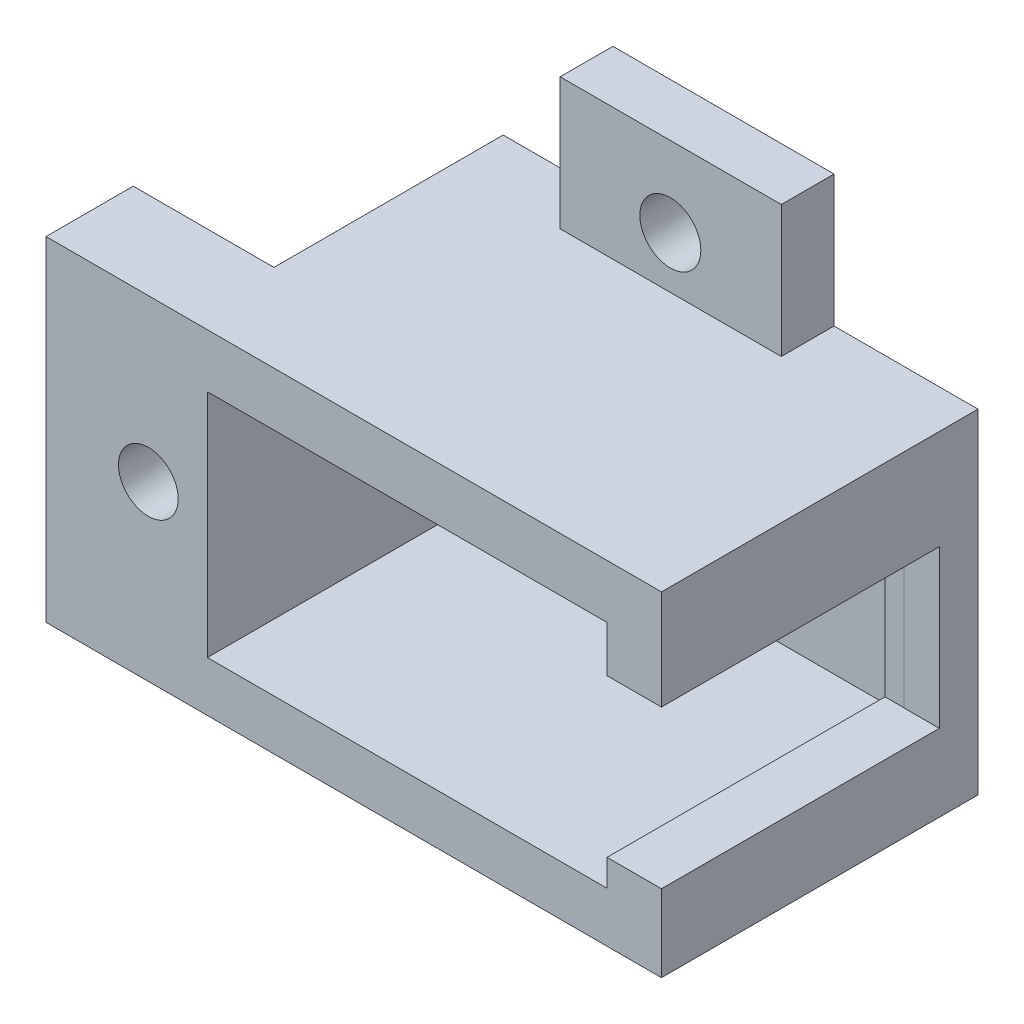
SolidWorks part; units mm, degrees
ref_plane "Front Plane" through (0, 0, 0) normal (0, 0, 1) x (1, 0, 0)
ref_plane "Top Plane" through (0, 0, 0) normal (0, 1, 0) x (1, 0, 0)
ref_plane "Right Plane" through (0, 0, 0) normal (1, 0, 0) x (0, 0, -1)
sketch "Sketch1" plane through (0, 0, 0) normal (0, 0, 1) x (1, 0, 0)
  line L1 (-1.0933, 0.8351) -> (1.4067, 0.8351)
  line L2 (-1.0933, 0.8351) -> (-1.0933, -0.6649)
  line L3 (-1.0933, -0.6649) -> (1.4067, -0.6649)
  line L4 (1.4067, 0.8351) -> (1.4067, -0.6649)
  dimension "D1" = 2.5
  dimension "D2" = 1.5
extrude "Boss-Extrude1" add sketch "Sketch1" along normal blind 1.8
sketch "Sketch2" plane through (0, 0, 1.8) normal (0, 0, 1) x (1, 0, 0)
  line L1 (-0.9755, 0.7298) -> (1.2972, 0.7298)
  line L2 (-0.9755, 0.7298) -> (-0.9755, -0.5795)
  line L3 (-0.9755, -0.5795) -> (1.2972, -0.5795)
  line L4 (1.2972, 0.7298) -> (1.2972, -0.5795)
extrude "Cut-Extrude1" cut sketch "Sketch2" against normal blind 1.7
sketch "Sketch3" plane through (1.4067, 0, 0) normal (1, 0, 0) x (0, 0, -1)
  line L1 (-0.2922, -0.4617) -> (-0.2902, -0.4617)
  line L2 (-0.2922, -0.4617) -> (-0.2922, -0.459)
  line L3 (-0.2922, -0.459) -> (-0.2902, -0.459)
  line L4 (-0.2902, -0.4617) -> (-0.2902, -0.459)
  line L5 (-0.2193, -0.427) -> (-1.6684, -0.427)
  line L6 (-0.2193, -0.427) -> (-0.2193, 0.4688)
  line L7 (-0.2193, 0.4688) -> (-1.6684, 0.4688)
  line L8 (-1.6684, -0.427) -> (-1.6684, 0.4688)
extrude "Cut-Extrude2" cut sketch "Sketch3" against normal blind 1.8
scale "Scale1" scale about centroid uniform scaling yes scale factor 10
sketch "Sketch6" plane through (13.765, 0, 0) normal (1, 0, 0) x (0, 0, -1)
  line L0 (-10.0899, -5.3785) -> (4.4011, -5.3785) construction
  line L1 (-12.7162, 3.5683) -> (-9.3169, 3.5683)
  line L2 (-12.7162, 3.5683) -> (-12.7162, -5.3785)
  line L3 (-12.7162, -5.3785) -> (-9.3169, -5.3785)
  line L4 (-9.3169, 3.5683) -> (-9.3169, -5.3785)
extrude "Cut-Extrude4" cut sketch "Sketch6" against normal blind 10
sketch "Sketch12" plane through (-11.235, 0, 0) normal (-1, 0, 0) x (0, 0, 1)
  line L1 (11.4058, 7.2418) -> (-6.5942, 7.2418) construction
  line L3 (6.4439, 7.2418) -> (11.4058, 7.2418)
  line L4 (6.4439, 7.2418) -> (6.4439, -7.7582)
  line L5 (6.4439, -7.7582) -> (11.4058, -7.7582)
  line L6 (11.4058, 7.2418) -> (11.4058, -7.7582)
extrude "Boss-Extrude5" add sketch "Sketch12" along normal blind 8
sketch "Sketch13" plane through (0, 0, 11.4058) normal (0, 0, 1) x (1, 0, 0)
  circle A0 centre (-13.4157, 0.0718) radius 1.6988
extrude "Cut-Extrude6" cut sketch "Sketch13" against normal blind 34 contours A0
sketch "Sketch22" plane through (0, 0, -6.5942) normal (0, 0, -1) x (-1, 0, 0)
  line L0 (-13.765, 7.2418) -> (11.235, 7.2418) construction
  line L1 (-7.5797, 7.2418) -> (5, 7.2418)
  line L2 (-7.5797, 7.2418) -> (-7.5797, 16.7274)
  line L3 (-7.5797, 16.7274) -> (5, 16.7274)
  line L4 (5, 7.2418) -> (5, 16.7274)
  line L5 (-13.765, -0.2582) -> (11.235, -0.2582) construction
  line L6 (-13.765, -7.7582) -> (-13.765, 7.2418) construction
  line L7 (11.235, 7.2418) -> (11.235, -7.7582) construction
  line L8 (-7.5797, -17.2437) -> (5, -17.2437)
  line L9 (5, -7.7582) -> (5, -17.2437)
  line L10 (-7.5797, -7.7582) -> (5, -7.7582)
  line L11 (-7.5797, -7.7582) -> (-7.5797, -17.2437)
extrude "Boss-Extrude10" add sketch "Sketch22" against normal blind 3
sketch "Sketch25" plane through (0, 0, -3.5942) normal (0, 0, 1) x (1, 0, 0)
  line L0 (-10.0573, -0.3569) -> (12.6698, -0.3569) construction
  line L1 (-10.0573, 6.1898) -> (-10.0573, -6.9036) construction
  line L2 (12.6698, -6.9036) -> (12.6698, 6.1898) construction
  circle A0 centre (1.2686, 12.1797) radius 1.7335
  circle A1 centre (1.2686, -12.8935) radius 1.7335
extrude "Cut-Extrude7" cut sketch "Sketch25" against normal blind 36
sketch "Sketch26" plane through (0, 7.2418, 0) normal (0, 1, 0) x (1, 0, 0)
  line L0 (13.765, -11.4058) -> (-19.235, -11.4058) construction
  line L1 (-11.235, 6.5942) -> (-4.9881, 6.5942)
  line L2 (-11.235, 6.5942) -> (-11.235, -11.4058)
  line L3 (-11.235, -11.4058) -> (-4.9881, -11.4058)
  line L4 (-4.9881, 6.5942) -> (-4.9881, -11.4058)
extrude "Boss-Extrude11" add sketch "Sketch26" along normal blind 2
sketch "Sketch27" plane through (0, 7.2418, 0) normal (0, 1, 0) x (1, 0, 0)
  line L0 (13.765, -11.4058) -> (-4.9881, -11.4058) construction
  line L1 (13.765, 6.5942) -> (7.5802, 6.5942)
  line L2 (13.765, 6.5942) -> (13.765, -11.4058)
  line L3 (13.765, -11.4058) -> (7.5802, -11.4058)
  line L4 (7.5802, 6.5942) -> (7.5802, -11.4058)
extrude "Boss-Extrude12" add sketch "Sketch27" along normal blind 2
sketch "Sketch28" plane through (0, 7.2418, 0) normal (0, 1, 0) x (1, 0, 0)
  line L1 (-5, 3.5942) -> (7.5802, 3.5942)
  line L2 (-5, 3.5942) -> (-5, -11.4058)
  line L3 (-5, -11.4058) -> (7.5802, -11.4058)
  line L4 (7.5802, 3.5942) -> (7.5802, -11.4058)
extrude "Boss-Extrude13" add sketch "Sketch28" along normal blind 2
sketch "Sketch29" plane through (0, -7.7582, 0) normal (0, -1, 0) x (-1, 0, 0)
  line L0 (19.235, -11.4058) -> (-13.765, -11.4058) construction
  line L1 (11.235, 6.5942) -> (5.0179, 6.5942)
  line L2 (11.235, 6.5942) -> (11.235, -11.4058)
  line L3 (11.235, -11.4058) -> (5.0179, -11.4058)
  line L4 (5.0179, 6.5942) -> (5.0179, -11.4058)
extrude "Boss-Extrude14" add sketch "Sketch29" along normal blind 2
sketch "Sketch30" plane through (0, -7.7582, 0) normal (0, -1, 0) x (-1, 0, 0)
  line L0 (5.0179, -11.4058) -> (-13.765, -11.4058) construction
  line L1 (-13.765, 6.5942) -> (-7.6155, 6.5942)
  line L2 (-13.765, 6.5942) -> (-13.765, -11.4058)
  line L3 (-13.765, -11.4058) -> (-7.6155, -11.4058)
  line L4 (-7.6155, 6.5942) -> (-7.6155, -11.4058)
extrude "Boss-Extrude15" add sketch "Sketch30" along normal blind 2
sketch "Sketch31" plane through (0, -7.7582, 0) normal (0, -1, 0) x (1, 0, 0)
  line L1 (-5.0179, 11.4058) -> (7.5797, 11.4058)
  line L2 (-5.0179, 11.4058) -> (-5.0179, -3.5942)
  line L3 (-5.0179, -3.5942) -> (7.5797, -3.5942)
  line L4 (7.5797, 11.4058) -> (7.5797, -3.5942)
extrude "Boss-Extrude16" add sketch "Sketch31" along normal blind 2
sketch "Sketch32" plane through (0, 7.2418, 0) normal (0, 1, 0) x (1, 0, 0)
  line L1 (-19.235, -6.4439) -> (-11.235, -6.4439)
  line L2 (-19.235, -6.4439) -> (-19.235, -11.4058)
  line L3 (-19.235, -11.4058) -> (-11.235, -11.4058)
  line L4 (-11.235, -6.4439) -> (-11.235, -11.4058)
extrude "Boss-Extrude17" add sketch "Sketch32" along normal blind 2
sketch "Sketch33" plane through (0, -7.7582, 0) normal (0, -1, 0) x (-1, 0, 0)
  line L1 (-7.5797, -11.4058) -> (-7.6155, -11.4058)
  line L2 (-7.5797, -11.4058) -> (-7.5797, 6.5942)
  line L3 (-7.5797, 6.5942) -> (-7.6155, 6.5942)
  line L4 (-7.6155, -11.4058) -> (-7.6155, 6.5942)
extrude "Boss-Extrude18" add sketch "Sketch33" along normal blind 2
sketch "Sketch34" plane through (0, -7.7582, 0) normal (0, -1, 0) x (1, 0, 0)
  line L1 (-19.235, 11.4058) -> (-11.235, 11.4058)
  line L2 (-19.235, 11.4058) -> (-19.235, 6.4439)
  line L3 (-19.235, 6.4439) -> (-11.235, 6.4439)
  line L4 (-11.235, 11.4058) -> (-11.235, 6.4439)
extrude "Boss-Extrude19" add sketch "Sketch34" along normal blind 2
sketch "Sketch36" plane through (13.765, 0, 0) normal (1, 0, 0) x (0, 0, -1)
  line L0 (6.5942, -9.7582) -> (6.5942, 9.2418) construction
  line L1 (-11.4058, -9.7582) -> (6.5942, -9.7582)
  line L2 (-11.4058, -9.7582) -> (-11.4058, -5.4407)
  line L3 (-11.4058, -5.4407) -> (6.5942, -5.4407)
  line L4 (6.5942, -9.7582) -> (6.5942, -5.4407)
extrude "Boss-Extrude20" add sketch "Sketch36" along normal blind 2
sketch "Sketch37" plane through (13.765, 0, 0) normal (1, 0, 0) x (0, 0, -1)
  line L0 (6.5942, -5.4407) -> (6.5942, 9.2418) construction
  line L1 (-11.4058, 9.2418) -> (6.5942, 9.2418)
  line L2 (-11.4058, 9.2418) -> (-11.4058, 3.6111)
  line L3 (-11.4058, 3.6111) -> (6.5942, 3.6111)
  line L4 (6.5942, 9.2418) -> (6.5942, 3.6111)
extrude "Boss-Extrude21" add sketch "Sketch37" along normal blind 2
sketch "Sketch38" plane through (13.765, 0, 0) normal (1, 0, 0) x (0, 0, -1)
  line L0 (6.5942, -5.4407) -> (-11.4058, -5.4407) construction
  line L1 (6.5942, 3.6111) -> (4.3948, 3.6111)
  line L2 (6.5942, 3.6111) -> (6.5942, -5.4407)
  line L3 (6.5942, -5.4407) -> (4.3948, -5.4407)
  line L4 (4.3948, 3.6111) -> (4.3948, -5.4407)
extrude "Boss-Extrude22" add sketch "Sketch38" along normal blind 2
sketch "Sketch39" plane through (13.765, 0, 0) normal (1, 0, 0) x (0, 0, -1)
  line L1 (-11.4058, 3.5683) -> (4.3948, 3.5683)
  line L2 (-11.4058, 3.5683) -> (-11.4058, 3.6111)
  line L3 (-11.4058, 3.6111) -> (4.3948, 3.6111)
  line L4 (4.3948, 3.5683) -> (4.3948, 3.6111)
extrude "Boss-Extrude23" add sketch "Sketch39" along normal blind 2
sketch "Sketch40" plane through (13.765, 0, 0) normal (1, 0, 0) x (0, 0, -1)
  line L1 (-11.4058, -5.4407) -> (4.3948, -5.4407)
  line L2 (-11.4058, -5.4407) -> (-11.4058, -5.3785)
  line L3 (-11.4058, -5.3785) -> (4.3948, -5.3785)
  line L4 (4.3948, -5.4407) -> (4.3948, -5.3785)
extrude "Boss-Extrude24" add sketch "Sketch40" along normal blind 2
sketch "Sketch42" plane through (0, 0, -3.5942) normal (0, 0, -1) x (-1, 0, 0)
  line L1 (5.0195, -7.9644) -> (5.0926, -7.9644)
  line L2 (5.0195, -7.9644) -> (5.0195, -9.9082)
  line L3 (5.0195, -9.9082) -> (5.0926, -9.9082)
  line L4 (5.0926, -7.9644) -> (5.0926, -9.9082)
